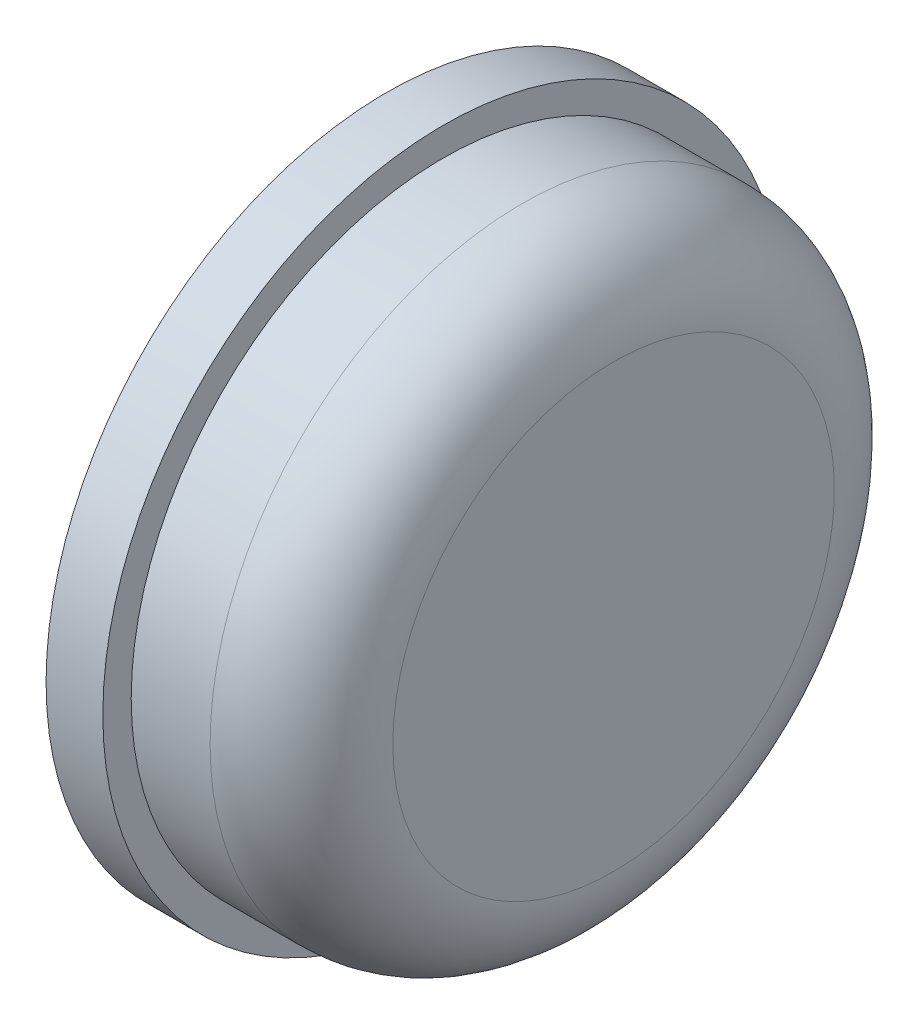
SolidWorks part; units mm, degrees
ref_plane "Front Plane" through (0, 0, 0) normal (0, 0, 1) x (1, 0, 0)
ref_plane "Top Plane" through (0, 0, 0) normal (0, 1, 0) x (1, 0, 0)
ref_plane "Right Plane" through (0, 0, 0) normal (1, 0, 0) x (0, 0, -1)
sketch "Sketch1" plane through (0, 0, 0) normal (0, 1, 0) x (1, 0, 0)
  line L0 (0, 0) -> (12311.6168, 0) construction
  line L1 (-10.839, 9.9792) -> (-10.839, 12)
  line L2 (-10.839, 12) -> (-8.839, 12)
  line L3 (-8.839, 12) -> (-8.839, 11)
  line L4 (-8.839, 11) -> (-6.0585, 11)
  line L5 (-2.839, 7.7805) -> (-2.839, 0)
  line L6 (-10.839, 0) -> (-2.839, 0)
  line L7 (-10.839, 9.9792) -> (-9.9996, 9.9792)
  line L8 (-10.54, 8.2855) -> (-9.7526, 6.2225)
  arc A0 (-6.0585, 11) -> (-2.839, 7.7805) centre (-6.0585, 7.7805) cw
  arc A1 (-9.9996, 9.9792) -> (-10.54, 8.2855) centre (-8.8878, 8.6913) ccw
  arc A2 (-9.7526, 6.2225) -> (-7.5844, 0) centre (-17.598, 0) cw
  dimension "D1" = 24
  dimension "D2" = 2
  dimension "D3" = 22
  dimension "D4" = 8
revolve "Revolve1" add sketch "Sketch1" angle 360 about L0
